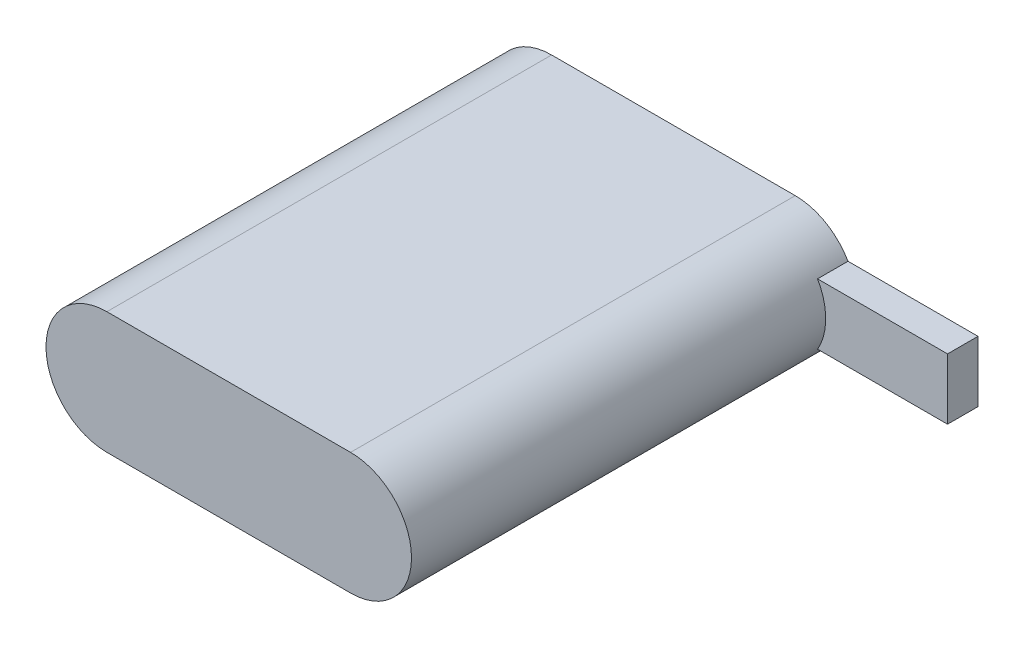
SolidWorks part; units mm, degrees
ref_plane "Front Plane" through (0, 0, 0) normal (0, 0, 1) x (1, 0, 0)
ref_plane "Top Plane" through (0, 0, 0) normal (0, 1, 0) x (1, 0, 0)
ref_plane "Right Plane" through (0, 0, 0) normal (1, 0, 0) x (0, 0, -1)
sketch "Sketch1" plane through (0, 0, 0) normal (0, 0, 1) x (1, 0, 0)
  line L0 (-20, -10) -> (20, -10)
  line L1 (20, 10) -> (-20, 10)
  line L2 (-30, 18.566) -> (-30, -20.9591) construction
  line L3 (-20, 0) -> (20, 0) construction
  line L4 (30, 17.406) -> (30, -18.639) construction
  arc A0 (-20, 10) -> (-20, -10) centre (-20, 0) ccw
  arc A1 (20, 10) -> (20, -10) centre (20, 0) cw
  dimension "D1" = 60
  dimension "D2" = 20
extrude "Boss-Extrude1" add sketch "Sketch1" along normal blind 73
sketch "Sketch2" plane through (0, 0, 0) normal (1, 0, 0) x (0, 0, -1)
  line L0 (0, -10) -> (0, 10) construction
  line L1 (-5, 5) -> (0, 5)
  line L2 (-5, 5) -> (-5, -5)
  line L3 (-5, -5) -> (0, -5)
  line L4 (0, 5) -> (0, -5)
  dimension "D1" = 5
  dimension "D2" = 10
extrude "Boss-Extrude2" add sketch "Sketch2" along normal blind 50
